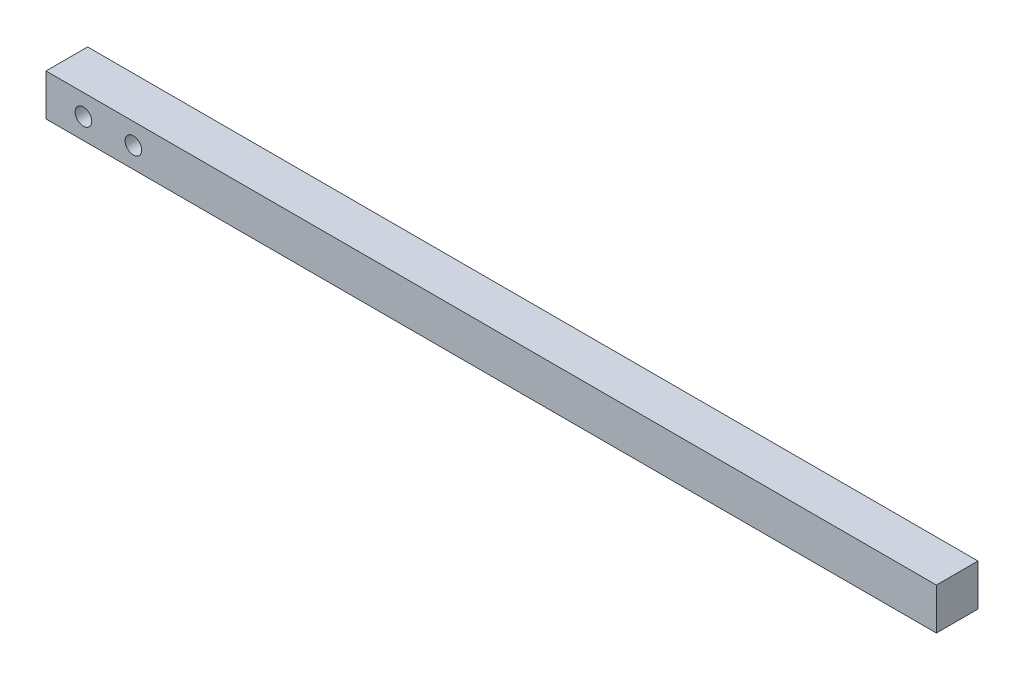
SolidWorks part; units mm, degrees
ref_plane "Спереди" through (0, 0, 0) normal (0, 0, 1) x (1, 0, 0)
ref_plane "Сверху" through (0, 0, 0) normal (0, 1, 0) x (1, 0, 0)
ref_plane "Справа" through (0, 0, 0) normal (1, 0, 0) x (0, 0, -1)
sketch "Эскиз1" plane through (0, 0, 0) normal (1, 0, 0) x (0, 0, -1)
  line L1 (-5, 5) -> (5, 5)
  line L2 (-5, 5) -> (-5, -5)
  line L3 (-5, -5) -> (5, -5)
  line L4 (5, 5) -> (5, -5)
  line L5 (-5, 5) -> (5, -5) construction
  line L6 (-5, -5) -> (5, 5) construction
  point P0 (0, 0)
extrude "Вытянуть1" add sketch "Эскиз1" along normal blind 214
sketch "Эскиз2" plane through (0, 0, 5) normal (0, 0, 1) x (1, 0, 0)
  line L0 (0, 0) -> (18.9811, 0) construction
  line L1 (30, 5) -> (30, -5) construction
  line L2 (21, 9.7565) -> (21, -16.8677) construction
  line L3 (9, 11.4183) -> (9, -15.7698) construction
  line L4 (0, 5) -> (0, -5) construction
  circle A0 centre (9, 0) radius 2
  circle A1 centre (21, 0) radius 2
  dimension "D1" = 9
  dimension "D2" = 9
extrude "Вырез-Вытянуть1" cut sketch "Эскиз2" against normal through all
